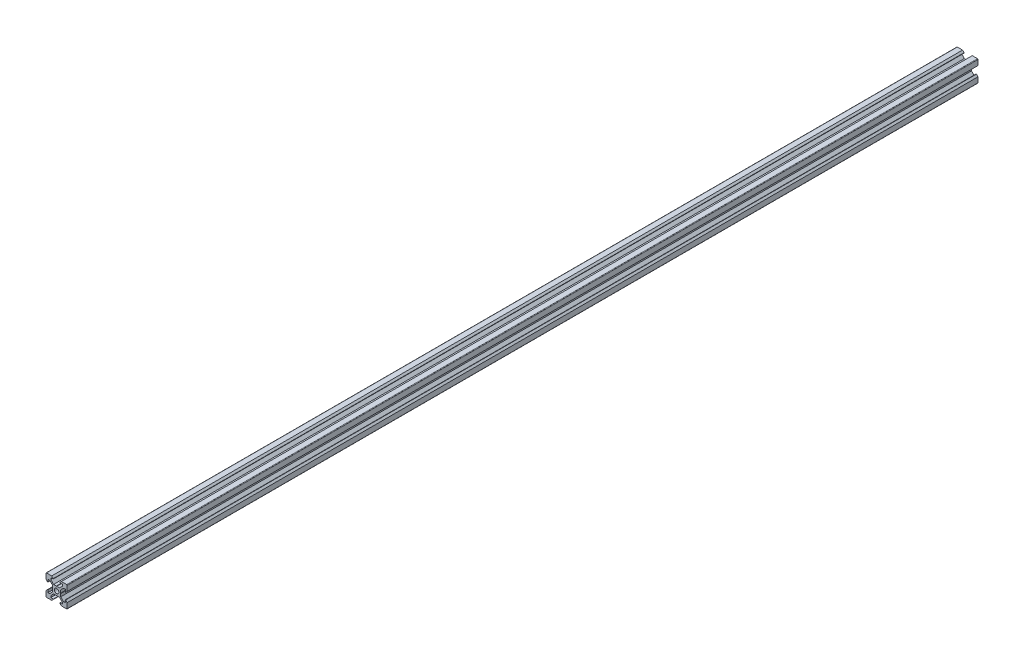
SolidWorks part; units mm, degrees
material "6061-T6 (SS)"
ref_plane "Front Plane" through (0, 0, 0) normal (0, 0, 1) x (1, 0, 0)
ref_plane "Top Plane" through (0, 0, 0) normal (0, 1, 0) x (1, 0, 0)
ref_plane "Right Plane" through (0, 0, 0) normal (1, 0, 0) x (0, 0, -1)
sketch "Sketch1" plane through (0, 0, 0) normal (0, 0, 1) x (1, 0, 0)
  line L1 (9.5, -10) -> (-9.5, -10)
  line L2 (10, -9.5) -> (10, 9.5)
  line L3 (9.5, 10) -> (-9.5, 10)
  line L4 (-10, -9.5) -> (-10, 9.5)
  line L5 (10, -10) -> (-10, 10) construction
  line L6 (10, 10) -> (-10, -10) construction
  circle A0 centre (0, 0) radius 2.1
  arc A1 (-9.5, 10) -> (-10, 9.5) centre (-9.5, 9.5) ccw
  arc A2 (10, 9.5) -> (9.5, 10) centre (9.5, 9.5) ccw
  arc A3 (9.5, -10) -> (10, -9.5) centre (9.5, -9.5) ccw
  arc A4 (-9.5, -10) -> (-10, -9.5) centre (-9.5, -9.5) cw
  point P0 (0, 0)
  line B0 (0, 0) -> (0, 10) construction
  line B1 (0, 3.69) -> (-0.21, 3.9)
  line B2 (-0.21, 3.9) -> (-2.8393, 3.9)
  line B3 (-2.8393, 3.9) -> (-5.5, 6.5607)
  line B4 (-5.5, 6.5607) -> (-5.5, 8.2)
  line B5 (-5.5, 8.2) -> (-3.125, 8.2)
  line B6 (-3.125, 8.2) -> (-3.125, 8.545)
  line B7 (-3.125, 8.545) -> (-4.58, 10)
  line B8 (-4.58, 10) -> (4.58, 10)
  line B9 (0, 0) -> (-5.9132, 5.9132) construction
  line B10 (3.125, 8.545) -> (4.58, 10)
  line B11 (3.125, 8.2) -> (3.125, 8.545)
  line B12 (5.5, 8.2) -> (3.125, 8.2)
  line B13 (5.5, 6.5607) -> (5.5, 8.2)
  line B14 (2.8393, 3.9) -> (5.5, 6.5607)
  line B15 (0.21, 3.9) -> (2.8393, 3.9)
  line B16 (0, 3.69) -> (0.21, 3.9)
  line B17 (0, 0) -> (-10, 0) construction
  line B18 (-3.69, 0) -> (-3.9, -0.21)
  line B19 (-3.9, -0.21) -> (-3.9, -2.8393)
  line B20 (-3.9, -2.8393) -> (-6.5607, -5.5)
  line B21 (-6.5607, -5.5) -> (-8.2, -5.5)
  line B22 (-8.2, -5.5) -> (-8.2, -3.125)
  line B23 (-8.2, -3.125) -> (-8.545, -3.125)
  line B24 (-8.545, -3.125) -> (-10, -4.58)
  line B25 (-10, -4.58) -> (-10, 4.58)
  line B26 (0, 0) -> (-5.9132, -5.9132) construction
  line B27 (-8.545, 3.125) -> (-10, 4.58)
  line B28 (-8.2, 3.125) -> (-8.545, 3.125)
  line B29 (-8.2, 5.5) -> (-8.2, 3.125)
  line B30 (-6.5607, 5.5) -> (-8.2, 5.5)
  line B31 (-3.9, 2.8393) -> (-6.5607, 5.5)
  line B32 (-3.9, 0.21) -> (-3.9, 2.8393)
  line B33 (-3.69, 0) -> (-3.9, 0.21)
  line B34 (0, 0) -> (0, -10) construction
  line B35 (0, -3.69) -> (0.21, -3.9)
  line B36 (0.21, -3.9) -> (2.8393, -3.9)
  line B37 (2.8393, -3.9) -> (5.5, -6.5607)
  line B38 (5.5, -6.5607) -> (5.5, -8.2)
  line B39 (5.5, -8.2) -> (3.125, -8.2)
  line B40 (3.125, -8.2) -> (3.125, -8.545)
  line B41 (3.125, -8.545) -> (4.58, -10)
  line B42 (4.58, -10) -> (-4.58, -10)
  line B43 (0, 0) -> (5.9132, -5.9132) construction
  line B44 (-3.125, -8.545) -> (-4.58, -10)
  line B45 (-3.125, -8.2) -> (-3.125, -8.545)
  line B46 (-5.5, -8.2) -> (-3.125, -8.2)
  line B47 (-5.5, -6.5607) -> (-5.5, -8.2)
  line B48 (-2.8393, -3.9) -> (-5.5, -6.5607)
  line B49 (-0.21, -3.9) -> (-2.8393, -3.9)
  line B50 (0, -3.69) -> (-0.21, -3.9)
  line B51 (0, 0) -> (10, 0) construction
  line B52 (3.69, 0) -> (3.9, 0.21)
  line B53 (3.9, 0.21) -> (3.9, 2.8393)
  line B54 (3.9, 2.8393) -> (6.5607, 5.5)
  line B55 (6.5607, 5.5) -> (8.2, 5.5)
  line B56 (8.2, 5.5) -> (8.2, 3.125)
  line B57 (8.2, 3.125) -> (8.545, 3.125)
  line B58 (8.545, 3.125) -> (10, 4.58)
  line B59 (10, 4.58) -> (10, -4.58)
  line B60 (0, 0) -> (5.9132, 5.9132) construction
  line B61 (8.545, -3.125) -> (10, -4.58)
  line B62 (8.2, -3.125) -> (8.545, -3.125)
  line B63 (8.2, -5.5) -> (8.2, -3.125)
  line B64 (6.5607, -5.5) -> (8.2, -5.5)
  line B65 (3.9, -2.8393) -> (6.5607, -5.5)
  line B66 (3.9, -0.21) -> (3.9, -2.8393)
  line B67 (3.69, 0) -> (3.9, -0.21)
  dimension "D1" = 4.2
  dimension "D3" = 0.5
  dimension "D2" = 20
sketch_block_instance "V Slot 1-4"
sketch_block "V Slot 1" parameters "D1"=10, "D2"=11, "D3"=4.3, "D4"=1.8, "D5"=0.21, "D6"=45, "D7"=9.16, "D8"=1.5, "D9"=6.25
sketch_block_instance "V Slot 1-5"
sketch_block_instance "V Slot 1-6"
sketch_block_instance "V Slot 1-7"
extrude "Boss-Extrude1" add sketch "Sketch1" along normal blind 860 contours B67 B52 B53 B54 B55 B56 B57 B58 L2 A2 L3 B10 B11 B12 B13 B14 B15 B16 B1 B2 B3 B4 B5 B6 B7 A1 L4 B27 B28 B29 B30 B31 B32 B33 B18 B19 B20 B21 B22 B23 B24 A4 L1 B44 B45 B46 B47 B48 B49
